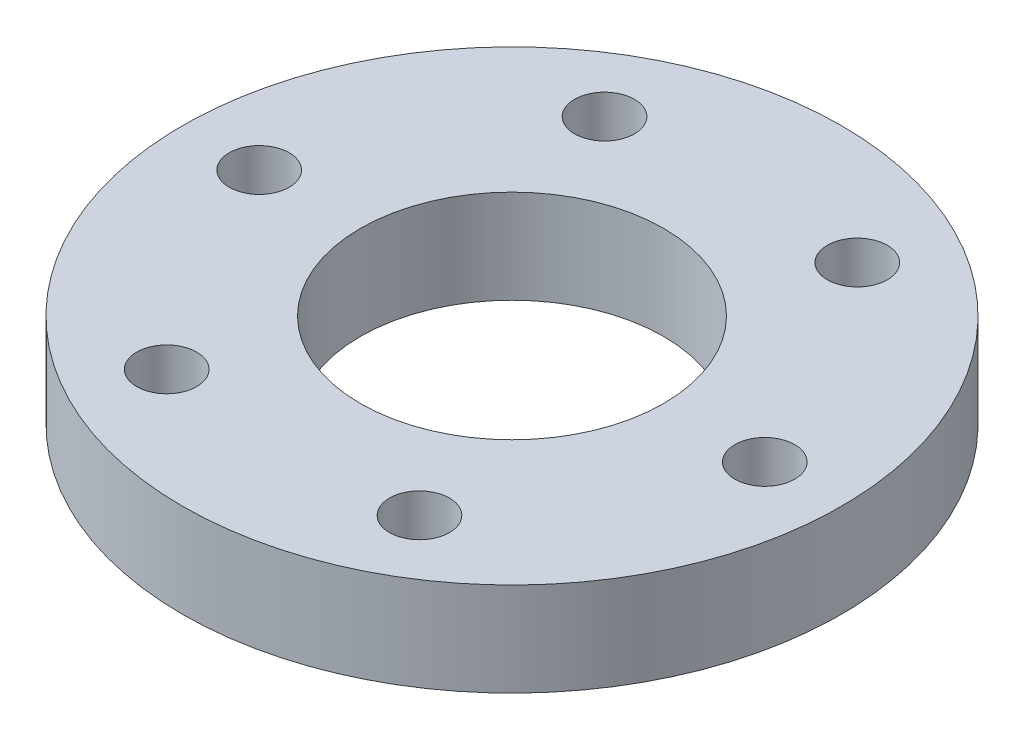
SolidWorks part; units mm, degrees
material "ABS"
ref_plane "Front Plane" through (0, 0, 0) normal (0, 0, 1) x (1, 0, 0)
ref_plane "Top Plane" through (0, 0, 0) normal (0, 1, 0) x (1, 0, 0)
ref_plane "Right Plane" through (0, 0, 0) normal (1, 0, 0) x (0, 0, -1)
sketch "Sketch1" plane through (0, 0, 0) normal (0, 1, 0) x (1, 0, 0)
  circle A0 centre (0, 0) radius 17.6
  circle A1 centre (0, 0) radius 8.1
  dimension "D1" = 35.2
  dimension "D2" = 16.2
extrude "Boss-Extrude1" add sketch "Sketch1" along normal blind 5
sketch "Sketch2" plane through (0, 0, 0) normal (0, -1, 0) x (1, 0, 0)
  line L0 (0, 0) -> (13.5, 0) construction
  line L1 (13.5, 3.2332) -> (10.7, 1.6166)
  line L2 (10.7, 1.6166) -> (10.7, -1.6166)
  line L3 (10.7, -1.6166) -> (13.5, -3.2332)
  line L4 (13.5, -3.2332) -> (16.3, -1.6166)
  line L5 (16.3, -1.6166) -> (16.3, 1.6166)
  line L6 (16.3, 1.6166) -> (13.5, 3.2332)
  circle A0 centre (13.5, 0) radius 2.8 construction
  dimension "D1" = 5.6
  dimension "D2" = 13.5
extrude "Cut-Extrude1" cut sketch "Sketch2" against normal blind 2.6
hole_wizard "M3 Clearance Hole1" positions "Sketch3" profile "Sketch4" hole size "M3" standard "ISO" end condition through all
sketch "Sketch3" plane through (0, 2.6, 0) normal (0, -1, 0) x (-1, 0, 0)
  point P0 (-13.5, 0)
sketch "Sketch4" plane through (13.5, 2.6, 0) normal (1, 0, 0) x (0, 0, -1)
  line L0 (0, 0) -> (0, 2.4)
  line L1 (0, 2.4) -> (1.6, 2.4)
  line L2 (1.6, 2.4) -> (1.6, 0)
  line L5 (1.6, 0) -> (0, 0)
  line L11 (0, -6.35) -> (0, 107.95) construction
  dimension "Thru Hole Dia." = 3.2
  dimension "Thru Hole Depth" = 2.4
pattern_circular "CirPattern1" count 6 over 360 about axis through (0, 0, 0) along (0, 1, 0) of "Cut-Extrude1", "M3 Clearance Hole1"
